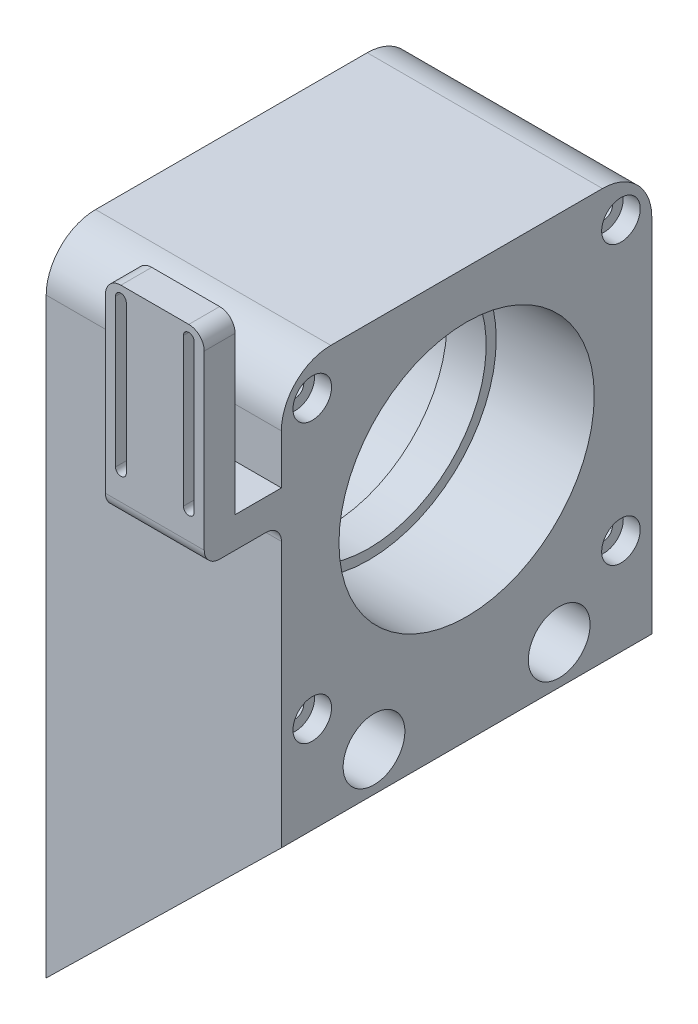
SolidWorks part; units mm, degrees
ref_plane "Front Plane" through (0, 0, 0) normal (0, 0, 1) x (1, 0, 0)
ref_plane "Top Plane" through (0, 0, 0) normal (0, 1, 0) x (1, 0, 0)
ref_plane "Right Plane" through (0, 0, 0) normal (1, 0, 0) x (0, 0, -1)
sketch "Sketch1" plane through (0, 0, 0) normal (0, 0, 1) x (1, 0, 0)
  line L0 (381, 457.2) -> (457.2, 457.2)
  line L1 (457.2, 457.2) -> (457.2, 431.8)
  line L2 (381, 457.2) -> (381, 357.2)
  line L5 (381, 357.2) -> (457.2, 431.8)
  dimension "D1" = 76.2
  dimension "D2" = 100
extrude "Boss-Extrude1" add sketch "Sketch1" along normal blind 120
sketch "Sketch3" plane through (457.2, 0, 0) normal (1, 0, 0) x (0, 0, -1)
  line L1 (-120, 431.8) -> (0, 431.8)
  line L2 (-120, 431.8) -> (-120, 357.2)
  line L3 (-120, 357.2) -> (0, 357.2)
  line L4 (0, 431.8) -> (0, 357.2)
  circle A0 centre (-90, 394.5) radius 4.25
  circle A1 centre (-30, 394.5) radius 4.25
  circle A2 centre (-90, 444.5) radius 4.25
  circle A3 centre (-30, 444.5) radius 4.25
  dimension "D1" = 30
  dimension "D2" = 30
  dimension "D3" = 37.3
  dimension "D4" = 37.3
extrude "Cut-Extrude1" cut sketch "Sketch3" against normal blind 120 contours A1 | A0
sketch "Sketch5" plane through (457.2, 0, 0) normal (1, 0, 0) x (0, 0, -1)
  circle A0 centre (-90, 394.5) radius 10
  circle A1 centre (-30, 394.5) radius 10
  circle A2 centre (-90, 444.5) radius 10
  circle A3 centre (-30, 444.5) radius 10
extrude "Cut-Extrude2" cut sketch "Sketch5" against normal blind 53
sketch "Sketch6" plane through (457.2, 0, 0) normal (1, 0, 0) x (0, 0, -1)
  circle A0 centre (-90, 444.5) radius 4.25
  circle A1 centre (-30, 444.5) radius 4.25
extrude "Cut-Extrude3" cut sketch "Sketch6" against normal blind 103
sketch "Sketch7" plane through (0, 457.2, 0) normal (0, 1, 0) x (1, 0, 0)
  line L1 (381, 0) -> (457.2, 0)
  line L2 (381, 0) -> (381, -120)
  line L3 (381, -120) -> (457.2, -120)
  line L4 (457.2, 0) -> (457.2, -120)
extrude "Boss-Extrude2" add sketch "Sketch7" along normal blind 101.6
sketch "Sketch8" plane through (381, 0, 0) normal (-1, 0, 0) x (0, 0, 1)
  line L0 (120, 457.2) -> (0, 457.2)
  line L1 (120, 558.8) -> (120, 357.2) construction
  line L2 (0, 558.8) -> (0, 357.2) construction
  line L3 (0, 558.8) -> (120, 558.8) construction
  circle A0 centre (60, 508) radius 41.35
  dimension "D1" = 101.6
  dimension "D2" = 50.8
extrude "Cut-Extrude4" cut sketch "Sketch8" against normal blind 31.75 contours A0
sketch "Sketch9" plane through (457.2, 0, 0) normal (1, 0, 0) x (0, 0, -1)
  line L0 (-120, 558.8) -> (0, 558.8) construction
  line L1 (-120, 431.8) -> (-120, 558.8) construction
  circle A0 centre (-60, 508) radius 41.35
  dimension "D1" = 50.8
  dimension "D2" = 60
extrude "Cut-Extrude5" cut sketch "Sketch9" against normal blind 31.75
sketch "Sketch10" plane through (457.2, 0, 0) normal (1, 0, 0) x (0, 0, -1)
  circle A0 centre (-60, 508) radius 38.1
extrude "Cut-Extrude6" cut sketch "Sketch10" against normal blind 76.2
sketch "Sketch13" plane through (0, 558.8, 0) normal (0, 1, 0) x (1, 0, 0)
  line L1 (381, 0) -> (457.2, 0)
  line L2 (381, 0) -> (381, -120)
  line L3 (381, -120) -> (457.2, -120)
  line L4 (457.2, 0) -> (457.2, -120)
extrude "Boss-Extrude3" add sketch "Sketch13" along normal blind 6
sketch "Sketch11" plane through (457.2, 0, 0) normal (1, 0, 0) x (0, 0, -1)
  line L0 (-120, 431.8) -> (-120, 564.8) construction
  line L1 (-110, 553) -> (-10, 553)
  line L2 (-110, 553) -> (-110, 463)
  line L3 (-110, 463) -> (-10, 463)
  line L4 (-10, 553) -> (-10, 463)
  line L5 (0, 431.8) -> (0, 564.8) construction
  circle A0 centre (-60, 508) radius 5.3331
  circle A1 centre (-110, 553) radius 2.75
  circle A2 centre (-10, 553) radius 2.75
  circle A3 centre (-10, 463) radius 2.75
  circle A4 centre (-110, 463) radius 2.75
  dimension "D1" = 10
  dimension "D2" = 10
  dimension "D3" = 45
  dimension "D4" = 90
extrude "Cut-Extrude7" cut sketch "Sketch11" against normal blind 84.4 contours L1 A1 L2 | L2 A1 L1 | L4 A2 L1 | L1 A2 L4 | L3 A3 L4 | L4 A3 L3 | L2 A4 L3 | L3 A4 L2
sketch "Sketch12" plane through (457.2, 0, 0) normal (1, 0, 0) x (0, 0, -1)
  circle A0 centre (-110, 553) radius 6.25
  circle A1 centre (-10, 553) radius 6.25
  circle A2 centre (-10, 463) radius 6.25
  circle A3 centre (-110, 463) radius 6.25
extrude "Cut-Extrude8" cut sketch "Sketch12" against normal blind 5.5
fillet "Fillet1" radius 16 2 edges at (419.1, 564.8, 0) (419.1, 564.8, 120)
sketch "Sketch17" plane through (0, 0, 120) normal (0, 0, 1) x (1, 0, 0)
  line L5 (428.45, 592.8) -> (428.45, 568.8)
  line L6 (457.2, 564.8) -> (425.2, 564.8)
  line L7 (457.2, 564.8) -> (457.2, 596.8)
  line L8 (457.2, 596.8) -> (425.2, 596.8)
  line L9 (425.2, 564.8) -> (425.2, 596.8)
  line L10 (431.95, 568.8) -> (431.95, 592.8)
  line L11 (450.45, 592.8) -> (450.45, 568.8)
  line L12 (453.95, 592.8) -> (453.95, 568.8)
  circle A4 centre (430.2, 592.8) radius 1.75
  circle A6 centre (430.2, 568.8) radius 1.75
  circle A7 centre (452.2, 568.8) radius 1.75
  circle A8 centre (452.2, 592.8) radius 1.75
  dimension "D3" = 22
  dimension "D1" = 32
  dimension "D2" = 32
  dimension "D4" = 22
  dimension "D5" = 5
  dimension "D6" = 5
  dimension "D7" = 4
  dimension "D8" = 4
  dimension "D9" = 4
  dimension "D10" = 4
sketch "Sketch18" plane through (0, 0, 120) normal (0, 0, 1) x (1, 0, 0)
  line L0 (457.2, 431.8) -> (457.2, 548.8) construction
  line L1 (457.2, 522.8) -> (425.2, 522.8)
  line L2 (457.2, 522.8) -> (457.2, 532.8)
  line L3 (457.2, 532.8) -> (425.2, 532.8)
  line L4 (425.2, 522.8) -> (425.2, 532.8)
  line L6 (381, 564.8) -> (457.2, 564.8) construction
  dimension "D1" = 32
  dimension "D2" = 32
  dimension "D3" = 10
extrude "Boss-Extrude6" add sketch "Sketch18" along normal blind 15
sketch "Sketch20" plane through (0, 0, 135) normal (0, 0, 1) x (1, 0, 0)
  line L0 (431.95, 584.6825) -> (431.95, 536.8)
  line L2 (425.2, 532.8) -> (425.2, 588.6825)
  line L3 (425.2, 588.6825) -> (457.2, 588.6825)
  line L4 (457.2, 536.6825) -> (457.2, 588.6825)
  line L5 (428.45, 584.6825) -> (428.45, 536.8)
  line L6 (450.45, 584.6825) -> (450.45, 536.8)
  line L7 (450.45, 584.6825) -> (450.45, 536.8)
  line L8 (425.2, 532.8) -> (425.2, 522.8)
  line L9 (425.2, 522.8) -> (457.2, 522.8)
  line L10 (457.2, 522.8) -> (457.2, 536.6825)
  line L11 (453.95, 584.6825) -> (453.95, 536.8)
  circle A0 centre (430.2, 584.6825) radius 1.75
  circle A1 centre (452.2, 584.6825) radius 1.75
  circle A2 centre (452.2, 536.8) radius 1.75
  circle A3 centre (430.2, 536.8) radius 1.75
  line M6 (457.2, 522.8) -> (457.2, 532.8)
  line M7 (457.2, 532.8) -> (425.2, 532.8)
  line M8 (425.2, 532.8) -> (425.2, 522.8)
  line M9 (425.2, 522.8) -> (457.2, 522.8)
  dimension "D1" = 22
  dimension "D2" = 22
  dimension "D3" = 5
  dimension "D4" = 52
  dimension "D5" = 4
  dimension "D6" = 5
  dimension "D7" = 4
extrude "Boss-Extrude7" add sketch "Sketch20" along normal blind 10 contours L4 L3 L2 A3 L5 A0 L0 A2 L6 A1 L7 M7 | M9 M6 M7 M8
fillet "Fillet3" radius 5 4 edges at (441.2, 522.8, 145) (425.2, 588.6825, 140) (457.2, 588.6825, 140) (441.2, 522.8, 120)
